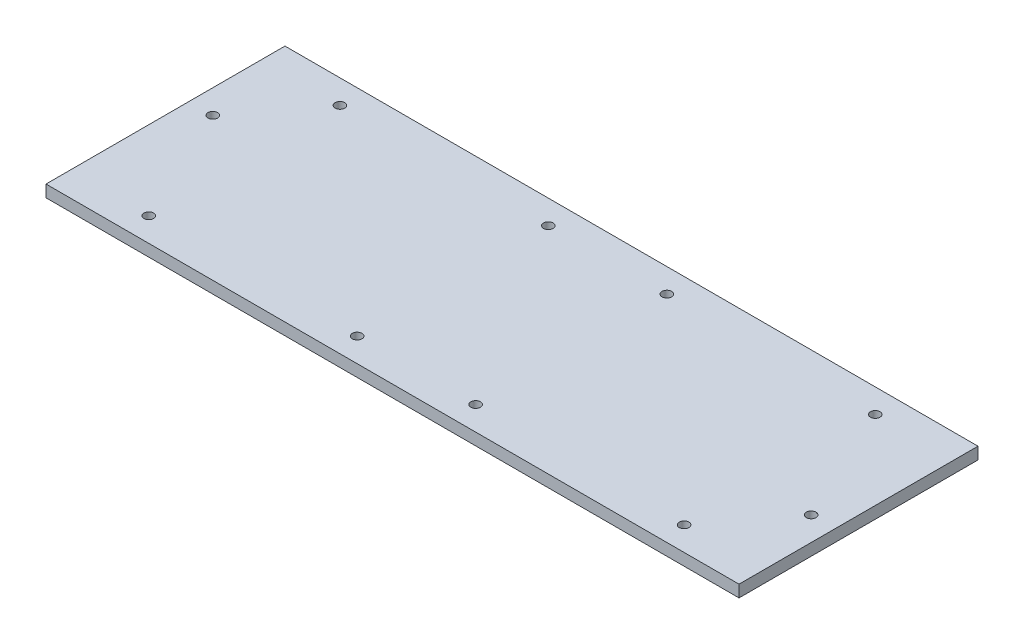
SolidWorks part; units mm, degrees
ref_plane "Front Plane" through (0, 0, 0) normal (0, 0, 1) x (1, 0, 0)
ref_plane "Top Plane" through (0, 0, 0) normal (0, 1, 0) x (1, 0, 0)
ref_plane "Right Plane" through (0, 0, 0) normal (1, 0, 0) x (0, 0, -1)
sketch "Sketch1" plane through (0, 0, 0) normal (0, 1, 0) x (1, 0, 0)
  line L0 (184.15, 0) -> (184.15, 127) construction
  line L1 (368.3, 127) -> (0, 127)
  line L2 (368.3, 127) -> (368.3, 0)
  line L3 (368.3, 0) -> (0, 0)
  line L4 (0, 127) -> (0, 0)
  line L6 (12.7, 114.3) -> (355.6, 114.3) construction
  line L7 (12.7, 114.3) -> (12.7, 12.7) construction
  line L8 (12.7, 12.7) -> (355.6, 12.7) construction
  line L9 (355.6, 114.3) -> (355.6, 12.7) construction
  line L10 (12.7, 114.3) -> (355.6, 12.7) construction
  line L11 (12.7, 12.7) -> (355.6, 114.3) construction
  circle A0 centre (326.39, 12.7) radius 2.5527
  circle A1 centre (41.91, 12.7) radius 2.5527
  circle A2 centre (41.91, 114.3) radius 2.5527
  circle A3 centre (326.39, 114.3) radius 2.5527
  circle A4 centre (215.646, 12.7) radius 2.5527
  circle A5 centre (152.654, 12.7) radius 2.5527
  circle A6 centre (215.646, 114.3) radius 2.5527
  circle A8 centre (152.654, 114.3) radius 2.5527
  circle A9 centre (12.7, 75.946) radius 2.5527
  circle A11 centre (355.6, 51.054) radius 2.5527
  point P7 (184.15, 63.5)
  dimension "D5" = 5.1054
  dimension "D6" = 152.654
  dimension "D7" = 41.91
  dimension "D8" = 5.1054
  dimension "D9" = 152.654
  dimension "D10" = 41.91
  dimension "D11" = 152.654
  dimension "D13" = 5.1054
  dimension "D15" = 5.1054
  dimension "D18" = 5.1054
  dimension "D19" = 152.654
  dimension "D21" = 5.1054
  dimension "D23" = 5.1054
  dimension "D20" = 5.1054
  dimension "D24" = 5.1054
  dimension "D25" = 5.1054
  dimension "D1" = 368.3
  dimension "D2" = 127
  dimension "D3" = 12.7
  dimension "D4" = 12.7
  dimension "D14" = 41.91
  dimension "D16" = 41.91
  dimension "D17" = 51.054
  dimension "D22" = 51.054
extrude "Boss-Extrude1" add sketch "Sketch1" along normal blind 6.35
